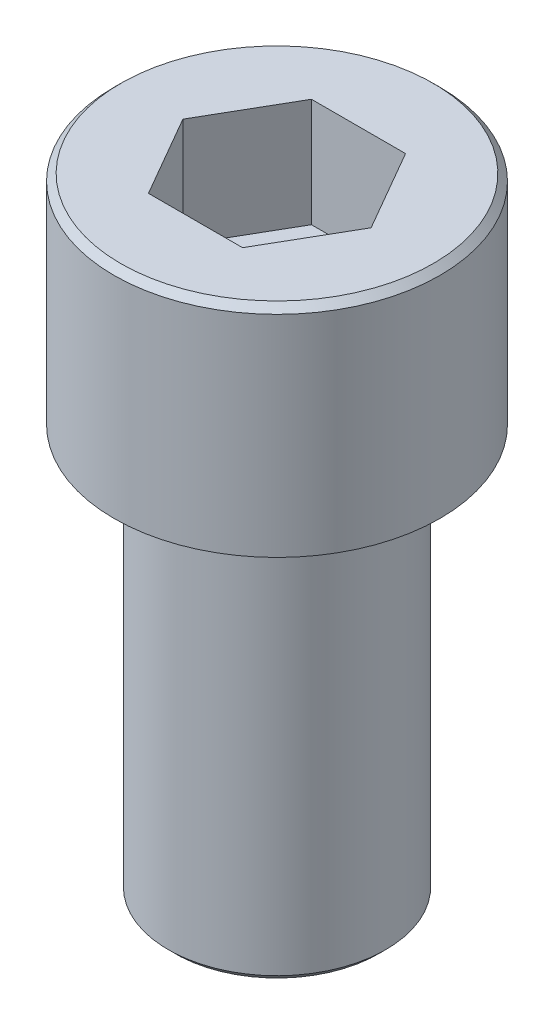
SolidWorks part; units mm, degrees
material "ASTM A574M"
ref_plane "Front" through (0, 0, 0) normal (0, 0, 1) x (1, 0, 0)
ref_plane "Base" through (0, 0, 0) normal (0, 1, 0) x (1, 0, 0)
ref_plane "Side" through (0, 0, 0) normal (1, 0, 0) x (0, 0, -1)
sketch "Sketch1" plane through (0, 0, 0) normal (0, 0, 1) x (1, 0, 0)
  line L0 (0, 0) -> (0, 28.4946) construction
  line L1 (0, 0) -> (8, 0)
  line L2 (8, 0) -> (8, 30)
  line L3 (8, 30) -> (12, 30)
  line L4 (12, 30) -> (12, 46)
  line L5 (12, 46) -> (0, 46)
  line L6 (0, 0) -> (0, 46)
  dimension "SCREW DIA" = 16
  dimension "HEAD DEPTH" = 16
  dimension "HEAD DIA" = 24
  dimension "SCREW LENGTH" = 30
revolve "Base-Revolve" add sketch "Sketch1" angle 360 about L0
sketch "Sketch2" plane through (0, 46, 0) normal (0, 1, 0) x (-1, 0, 0)
  line L0 (0, -4.7746) -> (0, 5.832) construction
  line L1 (5.9512, 0) -> (-5.4353, 0) construction
  line L2 (3.4641, -6) -> (-3.4641, -6)
  line L3 (-3.4641, -6) -> (-6.9282, 0)
  line L4 (3.4641, -6) -> (6.9282, 0)
  line L5 (3.4641, 6) -> (6.9282, 0)
  line L6 (-3.4641, 6) -> (-6.9282, 0)
  line L7 (3.4641, 6) -> (-3.4641, 6)
  dimension "HEX CUT LENGTH" = 12
  dimension "D2" = 120
extrude "Cut-Extrude1" cut sketch "Sketch2" against normal blind 8
chamfer "Chamfer1" distance 0.5 angle 45 2 edges at (0, 46, -12) (0, 0, -8)
sketch "Sketch3" plane through (0, 38, 0) normal (0, 1, 0) x (1, 0, 0)
  line L0 (-5.1962, -3) -> (5.1962, -3) construction
  line L1 (-3.4641, -6) -> (-6.9282, 0) construction
  line L2 (3.4641, -6) -> (6.9282, 0) construction
  text T0 "12.9 " font "Century Gothic" height 2.5
extrude "Cut-Extrude2" cut sketch "Sketch3" against normal blind 0.1
